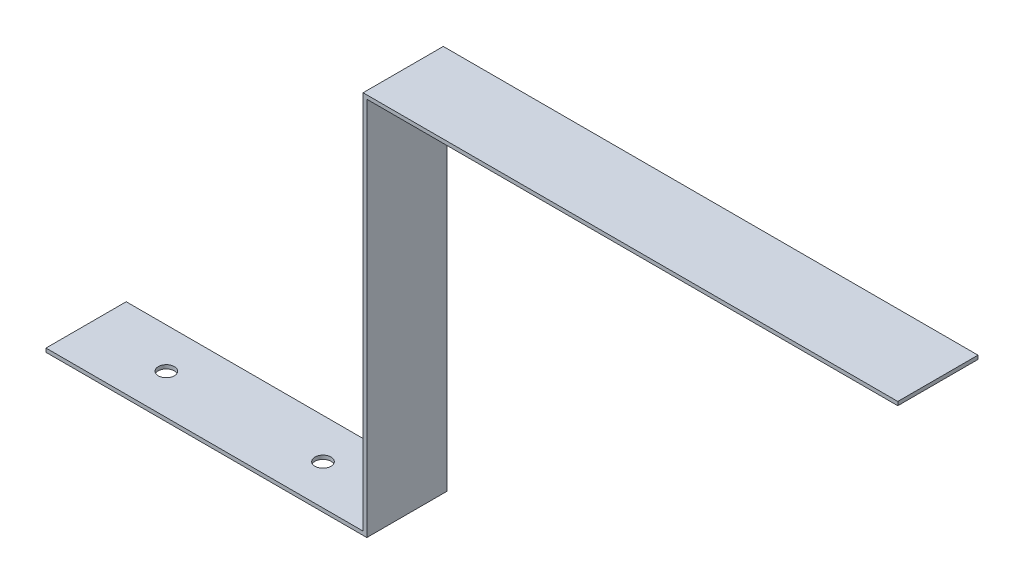
SolidWorks part; units mm, degrees
ref_plane "Front Plane" through (0, 0, 0) normal (0, 0, 1) x (1, 0, 0)
ref_plane "Top Plane" through (0, 0, 0) normal (0, 1, 0) x (1, 0, 0)
ref_plane "Right Plane" through (0, 0, 0) normal (1, 0, 0) x (0, 0, -1)
sketch "Sketch1" plane through (0, 0, 0) normal (0, 0, 1) x (1, 0, 0)
  line L0 (0, 0) -> (60, 0)
  line L1 (60, 0) -> (60, 71)
  line L2 (60, 71) -> (159.3, 71)
  line L3 (159.3, 71) -> (159.3, 71.7)
  line L4 (159.3, 71.7) -> (59.3, 71.7)
  line L5 (59.3, 71.7) -> (59.3, 0.7)
  line L6 (59.3, 0.7) -> (0, 0.7)
  line L7 (0, 0.7) -> (0, 0)
  point P9 (47.8003, 0)
  point P10 (48.3141, 76.0715)
  dimension "D1" = 71
  dimension "D2" = 60
  dimension "D3" = 0.7
  dimension "D4" = 0.7
  dimension "D5" = 0.7
  dimension "D6" = 100
extrude "Boss-Extrude1" add sketch "Sketch1" along normal blind 15
sketch "Sketch2" plane through (0, 0.7, 0) normal (0, 1, 0) x (1, 0, 0)
  line L0 (0, -7.5) -> (59.3, -7.5) construction
  line L1 (0, -15) -> (0, 0) construction
  line L2 (59.3, -15) -> (59.3, 0) construction
  circle A0 centre (15, -7.5) radius 1.5
  circle A1 centre (44.3, -7.5) radius 1.5
  dimension "D1" = 3
  dimension "D2" = 15
  dimension "D3" = 15
extrude "Cut-Extrude1" cut sketch "Sketch2" against normal through all
